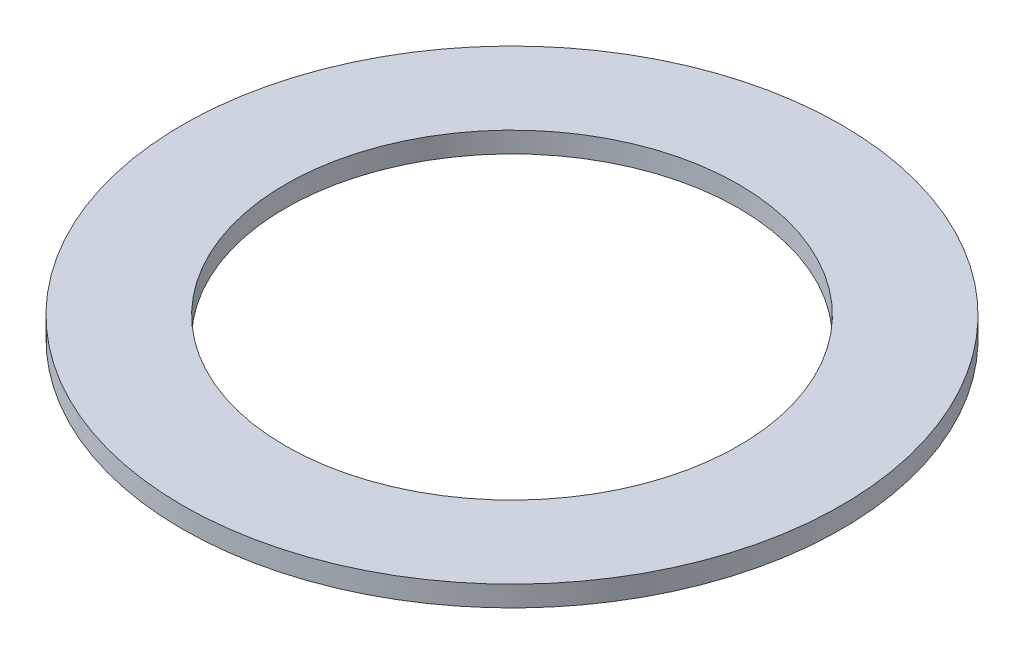
SolidWorks part; units mm, degrees
material "Plain Carbon Steel"
ref_plane "Front Plane" through (0, 0, 0) normal (0, 0, 1) x (1, 0, 0)
ref_plane "Top Plane" through (0, 0, 0) normal (0, 1, 0) x (1, 0, 0)
ref_plane "Right Plane" through (0, 0, 0) normal (1, 0, 0) x (0, 0, -1)
sketch "Sketch1" plane through (0, 0, 0) normal (0, 0, 1) x (1, 0, 0)
  line L0 (34.925, 0) -> (34.925, 3.175)
  line L1 (34.925, 3.175) -> (50.8, 3.175)
  line L2 (50.8, 3.175) -> (50.8, 0)
  line L3 (50.8, 0) -> (34.925, 0)
  line L4 (0, 0) -> (0, 14.5932) construction
  dimension "D1" = 34.925
  dimension "D2" = 50.8
  dimension "D3" = 3.175
revolve "Revolve1" add sketch "Sketch1" angle 360 about L4
